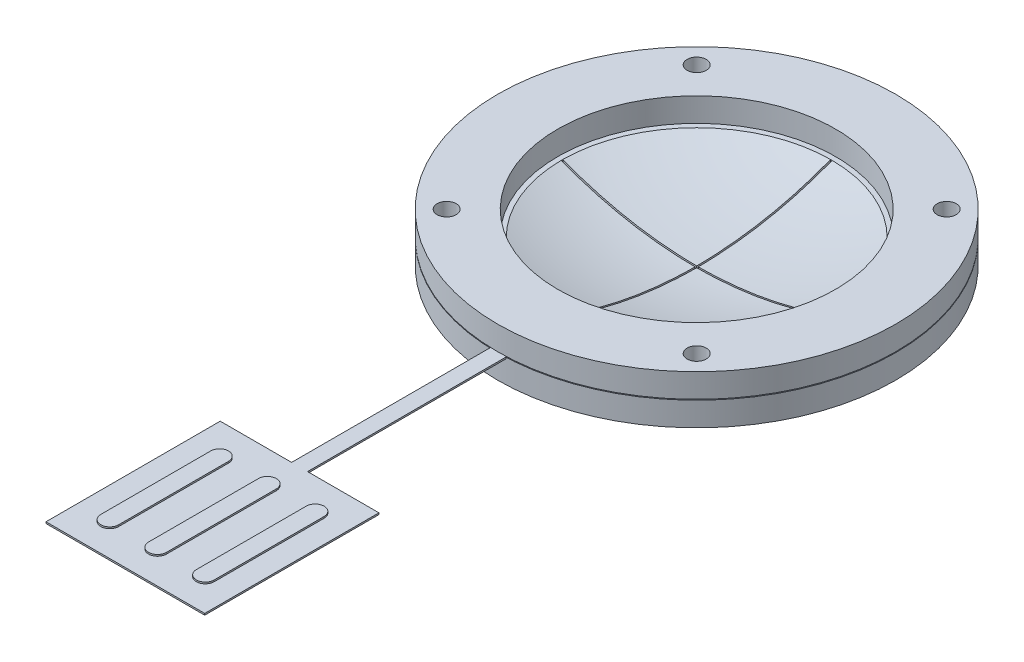
SolidWorks part; units mm, degrees
ref_plane "Ön Düzlem" through (0, 0, 0) normal (0, 0, 1) x (1, 0, 0)
ref_plane "Üst Düzlem" through (0, 0, 0) normal (0, 1, 0) x (1, 0, 0)
ref_plane "Sağ Düzlem" through (0, 0, 0) normal (1, 0, 0) x (0, 0, -1)
sketch "Çizim1" plane through (0, 0, 0) normal (1, 0, 0) x (0, 0, -1)
  line L0 (0, 0) -> (0, -21.82) construction
  line L1 (-84.5783, 0) -> (-99.9874, 0)
  line L2 (0, -21.82) -> (0, -15.82)
  arc A0 (-99.9874, 0) -> (0, -21.82) centre (0, 218.18) ccw
  arc A1 (-84.5783, 0) -> (0, -15.82) centre (0, 218.18) ccw
  circle A2 centre (0, 218.18) radius 240 construction
  circle A3 centre (0, 218.18) radius 234 construction
  point P3 (0, -21.82)
  dimension "D2" = 480
  dimension "D1" = 21.82
  dimension "D3" = 6
revolve "Döndür1" add sketch "Çizim1" angle 360 about L0
sketch "Çizim2" plane through (0, 0, 0) normal (0, 1, 0) x (1, 0, 0)
  line L0 (-0.5, -0.5) -> (-84.5768, -0.5)
  line L1 (0.5, -86.5218) -> (-0.5, -86.5218)
  line L2 (0.5, -86.5218) -> (0.5, -0.5)
  line L3 (0.5, 84.5768) -> (-0.5, 84.5768)
  line L4 (-0.5, -86.5218) -> (-0.5, -0.5)
  line L5 (0, 84.5768) -> (0, -86.5218) construction
  line L6 (0.5, 0) -> (-0.5, 0) construction
  line L7 (86.5218, -0.5) -> (0.5, -0.5)
  line L8 (86.5218, -0.5) -> (86.5218, 0.5)
  line L9 (86.5218, 0.5) -> (0.5, 0.5)
  line L10 (-84.5768, -0.5) -> (-84.5768, 0.5)
  line L11 (0, 0.5) -> (0, -0.5) construction
  line L12 (86.5218, 0) -> (-84.5768, 0) construction
  line L13 (0.5, 0.5) -> (0.5, 84.5768)
  line L14 (-0.5, 0.5) -> (-0.5, 84.5768)
  line L15 (-0.5, 0.5) -> (-84.5768, 0.5)
  circle A0 centre (0, 0) radius 84.5783 construction
  point P0 (0, 0)
  point P6 (0, 0)
  dimension "D1" = 1
  dimension "D2" = 1
extrude "Kes-Ekstrüzyon1" cut sketch "Çizim2" against normal up to next
sketch "Çizim3" plane through (0, 0, 0) normal (0, 1, 0) x (1, 0, 0)
  line L0 (-5, -249.3335) -> (-49.8237, -249.3335)
  line L1 (5, -95.8537) -> (-5, -95.8537)
  line L2 (5, -95.8537) -> (5, -249.3335)
  line L4 (-5, -95.8537) -> (-5, -249.3335)
  line L5 (0, -249.3335) -> (0, -95.8537) construction
  line L6 (5, -172.5936) -> (-5, -172.5936) construction
  line L7 (49.8237, -249.3335) -> (5, -249.3335)
  line L8 (49.8237, -249.3335) -> (49.8237, -358.7145)
  line L9 (49.8237, -358.7145) -> (-49.8237, -358.7145)
  line L10 (-49.8237, -249.3335) -> (-49.8237, -358.7145)
  line L11 (0, -358.7145) -> (0, -249.3335) construction
  line L12 (49.8237, -304.024) -> (-49.8237, -304.024) construction
  point P0 (0, -172.5936)
  point P5 (0, -304.024)
  dimension "D1" = 10
extrude "Yükseklik-Ekstrüzyon1" add sketch "Çizim3" against normal blind 1
sketch "Çizim4" plane through (0, 0, 0) normal (0, 1, 0) x (1, 0, 0)
  line L0 (30, -269.5217) -> (30, -338.5263) construction
  line L1 (35.6101, -269.5217) -> (35.6101, -338.5263)
  line L2 (24.3899, -269.5217) -> (24.3899, -338.5263)
  line L3 (0, -269.5217) -> (0, -338.5263) construction
  line L4 (5.6101, -269.5217) -> (5.6101, -338.5263)
  line L5 (-5.6101, -269.5217) -> (-5.6101, -338.5263)
  line L6 (-30, -269.5217) -> (-30, -338.5263) construction
  line L7 (-24.3899, -269.5217) -> (-24.3899, -338.5263)
  line L8 (-35.6101, -269.5217) -> (-35.6101, -338.5263)
  line L9 (49.8237, -358.7145) -> (49.8237, -249.3335) construction
  arc A0 (35.6101, -269.5217) -> (24.3899, -269.5217) centre (30, -269.5217) ccw
  arc A1 (24.3899, -338.5263) -> (35.6101, -338.5263) centre (30, -338.5263) ccw
  arc A2 (5.6101, -269.5217) -> (-5.6101, -269.5217) centre (0, -269.5217) ccw
  arc A3 (-5.6101, -338.5263) -> (5.6101, -338.5263) centre (0, -338.5263) ccw
  arc A4 (-24.3899, -269.5217) -> (-35.6101, -269.5217) centre (-30, -269.5217) ccw
  arc A5 (-35.6101, -338.5263) -> (-24.3899, -338.5263) centre (-30, -338.5263) ccw
  point P2 (30, -304.024)
  point P9 (0, -304.024)
  point P16 (-30, -304.024)
  point P28 (49.8237, -304.024)
  dimension "D1" = 30
  dimension "D2" = 30
extrude "Yükseklik-Ekstrüzyon2" add sketch "Çizim4" along normal blind 1
sketch "Çizim5" plane through (0, 0, 0) normal (0, 1, 0) x (1, 0, 0)
  line L0 (-0.5, 0.5) -> (-113.4839, 113.4839) construction
  line L1 (-113.4839, 113.4839) -> (-0.5, 0.5) construction
  line L2 (-0.5, 0.5) -> (-0.5, 169.7106) construction
  circle A0 centre (-0.5, 0.5) radius 125
  circle A1 centre (-0.5, 0.5) radius 87.2304
  circle A6 centre (-78.9889, 78.9889) radius 6
  circle A7 centre (77.9889, 78.9889) radius 6
  circle A8 centre (77.9889, -77.9889) radius 6
  circle A9 centre (-78.9889, -77.9889) radius 6
  dimension "D1" = 174.4607
  dimension "D2" = 250
  dimension "D3" = 45
  dimension "D4" = 12
  dimension "D5" = 111
  dimension "D7" = 111
  dimension "D6" = 4
extrude "Yükseklik-Ekstrüzyon4" add sketch "Çizim5" along normal blind 15 separate body
sketch "Çizim6" plane through (0, 0, 0) normal (0, -1, 0) x (1, 0, 0)
  line L0 (0, 0) -> (0, -166.8419) construction
  line L1 (0, 0) -> (133.5873, -133.5873) construction
  circle A0 centre (0, 0) radius 99.9874
  circle A2 centre (77.9889, -78.9889) radius 6
  circle A3 centre (0, 0) radius 125
  circle A4 centre (-78.9889, -78.9889) radius 6
  circle A5 centre (-78.9889, 77.9889) radius 6
  circle A6 centre (77.9889, 77.9889) radius 6
  dimension "D1" = 199.9749
  dimension "D2" = 250
  dimension "D4" = 12
  dimension "D3" = 45
extrude "Yükseklik-Ekstrüzyon6" add sketch "Çizim6" along normal blind 15 separate body
